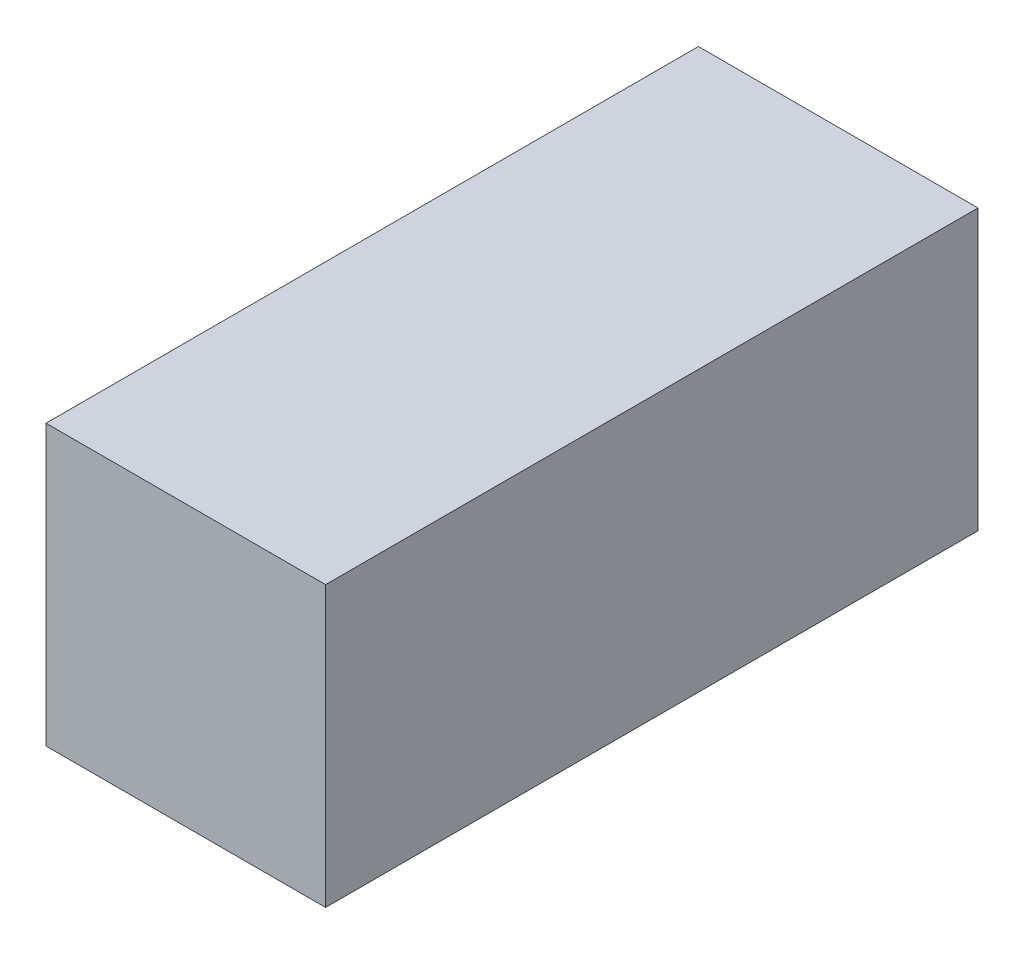
SolidWorks part; units mm, degrees
material "1060 Alloy"
ref_plane "Front Plane" through (0, 0, 0) normal (0, 0, 1) x (1, 0, 0)
ref_plane "Top Plane" through (0, 0, 0) normal (0, 1, 0) x (1, 0, 0)
ref_plane "Right Plane" through (0, 0, 0) normal (1, 0, 0) x (0, 0, -1)
sketch "Sketch1" plane through (0, 0, 0) normal (0, 0, 1) x (1, 0, 0)
  line L1 (15, 15) -> (-15, 15)
  line L2 (15, 15) -> (15, -15)
  line L3 (15, -15) -> (-15, -15)
  line L4 (-15, 15) -> (-15, -15)
  line L5 (15, 15) -> (-15, -15) construction
  line L6 (15, -15) -> (-15, 15) construction
  point P0 (0, 0)
  dimension "D1" = 30
  dimension "D2" = 30
extrude "Boss-Extrude1" add sketch "Sketch1" along normal blind 70
